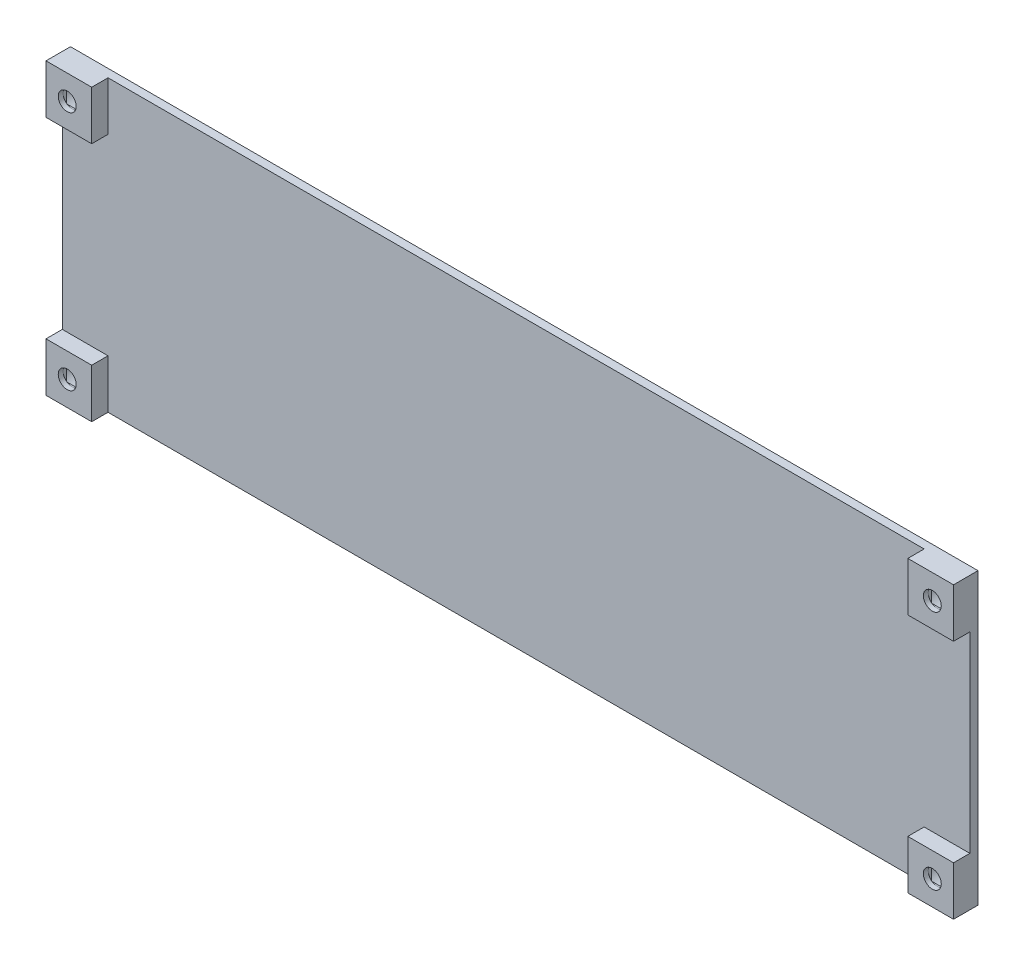
SolidWorks part; units mm, degrees
ref_plane "Front Plane" through (0, 0, 0) normal (0, 0, 1) x (1, 0, 0)
ref_plane "Top Plane" through (0, 0, 0) normal (0, 1, 0) x (1, 0, 0)
ref_plane "Right Plane" through (0, 0, 0) normal (1, 0, 0) x (0, 0, -1)
sketch "Sketch1" plane through (0, 0, 0) normal (0, 0, 1) x (1, 0, 0)
  line L1 (-56, -17.75) -> (56, -17.75)
  line L2 (-56, -17.75) -> (-56, 17.75)
  line L3 (-56, 17.75) -> (56, 17.75)
  line L4 (56, -17.75) -> (56, 17.75)
  line L5 (-56, -17.75) -> (56, 17.75) construction
  line L6 (-56, 17.75) -> (56, -17.75) construction
  point P0 (0, 0)
  dimension "D1" = 112
  dimension "D2" = 35.5
extrude "Boss-Extrude1" add sketch "Sketch1" along normal blind 1
sketch "Sketch2" plane through (0, 0, 1) normal (0, 0, 1) x (1, 0, 0)
  line L0 (0, -17.75) -> (0, 17.75) construction
  line L1 (-56, 17.75) -> (-50, 17.75)
  line L2 (-56, 17.75) -> (-56, 11.75)
  line L3 (-56, 11.75) -> (-50, 11.75)
  line L4 (-50, 17.75) -> (-50, 11.75)
  line L5 (-56, -17.75) -> (56, -17.75) construction
  line L6 (56, 17.75) -> (-56, 17.75) construction
  line L7 (-56, 0) -> (56, 0) construction
  line L8 (-56, 17.75) -> (-56, -17.75) construction
  line L9 (56, -17.75) -> (56, 17.75) construction
  line L10 (-50, -17.75) -> (-50, -11.75)
  line L11 (-56, -11.75) -> (-50, -11.75)
  line L12 (-56, -17.75) -> (-56, -11.75)
  line L13 (-56, -17.75) -> (-50, -17.75)
  line L14 (56, -17.75) -> (50, -17.75)
  line L15 (56, -17.75) -> (56, -11.75)
  line L16 (56, -11.75) -> (50, -11.75)
  line L17 (50, -17.75) -> (50, -11.75)
  line L18 (50, 17.75) -> (50, 11.75)
  line L19 (56, 11.75) -> (50, 11.75)
  line L20 (56, 17.75) -> (56, 11.75)
  line L21 (56, 17.75) -> (50, 17.75)
  dimension "D1" = 6
extrude "Boss-Extrude2" add sketch "Sketch2" along normal blind 2
sketch "Sketch3" plane through (0, 0, 3) normal (0, 0, 1) x (1, 0, 0)
  line L0 (-56, 0) -> (56, 0) construction
  line L1 (-56, 11.75) -> (-56, -11.75) construction
  line L2 (56, -11.75) -> (56, 11.75) construction
  line L3 (0, 17.75) -> (0, -17.75) construction
  line L4 (50, 17.75) -> (-50, 17.75) construction
  line L5 (-50, -17.75) -> (50, -17.75) construction
  line L6 (-56, 11.75) -> (-50, 17.75) construction
  line L7 (-56, -11.75) -> (-50, -17.75) construction
  line L8 (56, -11.75) -> (50, -17.75) construction
  line L9 (56, 11.75) -> (50, 17.75) construction
  circle A0 centre (-53, 14.75) radius 1.1
  circle A1 centre (-53, -14.75) radius 1.1
  circle A2 centre (53, -14.75) radius 1.1
  circle A3 centre (53, 14.75) radius 1.1
  dimension "D1" = 2.2
extrude "Cut-Extrude1" cut sketch "Sketch3" against normal through all
sketch "Sketch4" plane through (0, 0, 0) normal (0, 0, -1) x (-1, 0, 0)
  circle A0 centre (-53, 14.75) radius 2
  circle A1 centre (-53, -14.75) radius 2
  circle A2 centre (53, 14.75) radius 2
  circle A3 centre (53, -14.75) radius 2
  dimension "D1" = 4
extrude "Cut-Extrude2" cut sketch "Sketch4" against normal blind 2
sketch "Sketch5" plane through (0, 0, 2) normal (0, 0, -1) x (-1, 0, 0)
  line L2 (-54.1, 13.0797) -> (-54.1, 16.4203)
  line L4 (-51.9, 13.0797) -> (-51.9, 16.4203)
  line L5 (-54.1, 13.0797) -> (-51.9, 16.4203) construction
  line L6 (-54.1, 16.4203) -> (-51.9, 13.0797) construction
  circle A0 centre (-53, 14.75) radius 2 construction
  circle A1 centre (-53, 14.75) radius 1.1 construction
  circle A2 centre (-53, 14.75) radius 2 construction
  arc A3 (-51.9, 16.4203) -> (-54.1, 16.4203) centre (-53, 14.75) ccw
  arc A4 (-54.1, 13.0797) -> (-51.9, 13.0797) centre (-53, 14.75) ccw
  point P0 (-53, 14.75)
extrude "Cut-Extrude3" cut sketch "Sketch5" against normal blind 0.2
sketch "Sketch6" plane through (0, 0, 2.2) normal (0, 0, -1) x (-1, 0, 0)
  line L0 (-51.9, 13.0797) -> (-51.9, 16.4203) construction
  line L1 (-54.1, 13.65) -> (-51.9, 13.65)
  line L2 (-54.1, 13.65) -> (-54.1, 15.85)
  line L3 (-54.1, 15.85) -> (-51.9, 15.85)
  line L4 (-51.9, 13.65) -> (-51.9, 15.85)
  line L5 (-54.1, 13.65) -> (-51.9, 15.85) construction
  line L6 (-54.1, 15.85) -> (-51.9, 13.65) construction
  arc A0 (-51.9, 14.75) -> (-54.1, 14.75) centre (-53, 14.75) ccw construction
  point P0 (-53, 14.75)
extrude "Cut-Extrude4" cut sketch "Sketch6" against normal blind 0.2
mirror "Mirror1" about plane through (0, 0, 0) normal (1, 0, 0) of "Cut-Extrude4", "Cut-Extrude3"
mirror "Mirror2" about plane through (0, 0, 0) normal (0, 1, 0) of "Mirror1", "Cut-Extrude3", "Cut-Extrude4"
sketch "Sketch7" plane through (0, 0, 0) normal (0, 0, -1) x (-1, 0, 0)
  line L0 (56, -17.75) -> (-56, -17.75) construction
  line L1 (-56, 17.75) -> (-55.6, 17.75)
  line L2 (-56, 17.75) -> (-56, -17.75)
  line L3 (-56, -17.75) -> (-55.6, -17.75)
  line L4 (-55.6, 17.75) -> (-55.6, -17.75)
  line L6 (56, 17.75) -> (55.6, 17.75)
  line L7 (56, 17.75) -> (56, -17.75)
  line L8 (56, -17.75) -> (55.6, -17.75)
  line L9 (55.6, 17.75) -> (55.6, -17.75)
  dimension "D1" = 0.4
extrude "Cut-Extrude5" cut sketch "Sketch7" against normal through all
sketch "Sketch8" plane through (0, 0, 0) normal (0, 0, -1) x (-1, 0, 0)
  line L0 (-55.6, 17.75) -> (55.6, -17.75) construction
  line L1 (-12.5869, -14.75) -> (0, -14.75) construction
  line L2 (55.6, -17.75) -> (-55.6, -17.75) construction
  line L3 (0, 17.75) -> (0, -17.75) construction
  line L4 (-55.6, 17.75) -> (55.6, 17.75) construction
  text T0 "2" font "@HarmonyOS Sans SC" height 28
  point P6 (0, 0)
  point P14 (-11.3282, -14.75)
  point P15 (-16.5919, -14.75)
  point P16 (-12.5869, -14.75)
  dimension "D1" = 3
extrude "Cut-Extrude6" cut sketch "Sketch8" against normal blind 0.2
sketch "Sketch9" plane through (0, 0, 0.2) normal (0, 0, -1) x (-1, 0, 0)
  line L14 (-2.8287, -9.9915) -> (2.102, -4.5072)
  line L15 (-2.8287, -9.9915) -> (2.102, -4.5072)
  line L16 (-2.1866, -1.7351) -> (-10.611, -11.1912)
  line L17 (-10.611, -11.1912) -> (-10.611, -14.65)
  line L18 (-10.611, -14.65) -> (8.5012, -14.65)
  line L19 (8.5012, -14.65) -> (8.5012, -9.9915)
  line L20 (8.5012, -9.9915) -> (-2.8287, -9.9915)
  line L23 (-2.1866, -1.7351) -> (-10.611, -11.1912)
  line L24 (-10.611, -11.1912) -> (-10.611, -14.65)
  line L25 (-10.611, -14.65) -> (8.5012, -14.65)
  line L26 (8.5012, -14.65) -> (8.5012, -9.9915)
  line L27 (8.5012, -9.9915) -> (-2.8287, -9.9915)
  line L28 (-10.7074, 6.7941) -> (-6.5233, 4.3675)
  line L29 (-10.7074, 6.7941) -> (-6.5233, 4.3675)
  spline S6 degree 3 poles (134.6754, 999.4395) (-22.4629, -20.1233) (-9.21, 9.9871) (-0.8114, 8.7043) (-0.5784, 8.6407) (-0.1271, 8.4642) (0.086, 8.3541) (0.4813, 8.0795) (0.663, 7.9142) (0.9853, 7.5568) (1.1295, 7.3602) (1.3683, 6.939) (1.4627, 6.718) (1.6114, 6.2594) (1.6646, 6.0208) (2.787, -3.066) (-25.3418, -15.1284) (998.2361, 88.5106) knots -4.199783 -4.199783 -4.199783 -4.199783 0.125 0.125 0.25 0.25 0.375 0.375 0.5 0.5 0.625 0.625 0.75 0.75 0.875 0.875 5.500499 5.500499 5.500499 5.500499 only from (-1.7636, 8.7959) to (1.74, 5.0597)
  spline S7 degree 3 poles (-1.7636, 8.7959) (-1.5234, 8.7862) (-1.2832, 8.7764) (-0.8114, 8.7043) (-0.5784, 8.6407) (-0.1271, 8.4642) (0.086, 8.3541) (0.4813, 8.0795) (0.663, 7.9142) (0.9853, 7.5568) (1.1295, 7.3602) (1.3683, 6.939) (1.4627, 6.718) (1.6114, 6.2594) (1.6646, 6.0208) (1.7236, 5.5426) (1.7318, 5.3011) (1.74, 5.0597) knots 0 0 0 0 0.125 0.125 0.25 0.25 0.375 0.375 0.5 0.5 0.625 0.625 0.75 0.75 0.875 0.875 1 1 1 1
  spline S8 degree 3 poles (987.5147, -163.0057) (-15.912, 26.4068) (2.4814, 13.5857) (1.6962, 4.3911) (1.6745, 4.226) (1.5805, 3.7367) (1.4834, 3.4173) (1.1061, 2.476) (0.7514, 1.9108) (0.1676, 1.0972) (-0.0368, 0.8319) (-0.4521, 0.3062) (-0.6602, 0.0437) (-17.2797, -20.0408) (-56.7033, -20.5267) (712.8802, -700.7896) knots -3.326313 -3.326313 -3.326313 -3.326313 0.0625 0.0625 0.125 0.125 0.25 0.25 0.5 0.5 0.625 0.625 0.75 0.75 10.356881 10.356881 10.356881 10.356881 only from (1.74, 5.0597) to (-2.1866, -1.7351)
  spline S9 degree 3 poles (1.74, 5.0597) (1.7323, 4.8919) (1.7246, 4.7241) (1.6962, 4.3911) (1.6745, 4.226) (1.5805, 3.7367) (1.4834, 3.4173) (1.1061, 2.476) (0.7514, 1.9108) (0.1676, 1.0972) (-0.0368, 0.8319) (-0.4521, 0.3062) (-0.6602, 0.0437) (-1.3006, -0.7302) (-1.7431, -1.233) (-2.1866, -1.7351) knots 0 0 0 0 0.0625 0.0625 0.125 0.125 0.25 0.25 0.5 0.5 0.625 0.625 0.75 0.75 1 1 1 1
  spline S10 degree 3 poles (711.026, -709.7907) (-45.727, -28.2949) (-13.4715, -22.6013) (3.3616, -3.0687) (3.6685, -2.7022) (4.2695, -1.9583) (4.5642, -1.582) (5.142, -0.8207) (5.4158, -0.429) (5.9442, 0.3687) (6.1932, 0.7759) (6.6239, 1.6215) (6.8069, 2.0598) (7.0282, 2.7427) (7.0935, 2.9743) (7.2061, 3.4383) (7.2532, 3.6715) (9.2852, 16.9529) (-30.4418, 35.965) (1001.9812, -98.3208) knots -6.493203 -6.493203 -6.493203 -6.493203 0.125 0.125 0.25 0.25 0.375 0.375 0.5 0.5 0.625 0.625 0.75 0.75 0.8125 0.8125 0.875 0.875 4.346627 4.346627 4.346627 4.346627 only from (2.102, -4.5072) to (7.3944, 5.3314)
  spline S11 degree 3 poles (2.102, -4.5072) (2.4198, -4.1501) (2.7375, -3.7928) (3.3616, -3.0687) (3.6685, -2.7022) (4.2695, -1.9583) (4.5642, -1.582) (5.142, -0.8207) (5.4158, -0.429) (5.9442, 0.3687) (6.1932, 0.7759) (6.6239, 1.6215) (6.8069, 2.0598) (7.0282, 2.7427) (7.0935, 2.9743) (7.2061, 3.4383) (7.2532, 3.6715) (7.361, 4.3762) (7.3788, 4.8537) (7.3944, 5.3314) knots 0 0 0 0 0.125 0.125 0.25 0.25 0.375 0.375 0.5 0.5 0.625 0.625 0.75 0.75 0.8125 0.8125 0.875 0.875 1 1 1 1
  spline S12 degree 3 poles (998.9416, 135.0241) (-13.1864, -24.171) (8.262, -7.0923) (7.338, 6.4538) (7.3076, 6.7317) (7.172, 7.5575) (7.0242, 8.0996) (6.6173, 9.1596) (6.3658, 9.6622) (5.7547, 10.6058) (5.3883, 11.0491) (4.5734, 11.8215) (4.1245, 12.159) (3.1504, 12.7444) (2.6394, 12.9802) (1.8421, 13.2558) (1.5718, 13.3366) (1.0193, 13.4683) (0.741, 13.5177) (0.1833, 13.6038) (-0.0968, 13.6357) (-12.5963, 14.4477) (-27.6337, -10.3518) (72.5754, 1010.9536) knots -2.90139 -2.90139 -2.90139 -2.90139 0.0625 0.0625 0.125 0.125 0.25 0.25 0.375 0.375 0.5 0.5 0.625 0.625 0.75 0.75 0.8125 0.8125 0.875 0.875 0.9375 0.9375 3.649243 3.649243 3.649243 3.649243 only from (7.3944, 5.3314) to (-1.2263, 13.6812)
  spline S13 degree 3 poles (7.3944, 5.3314) (7.3853, 5.6129) (7.3762, 5.8943) (7.338, 6.4538) (7.3076, 6.7317) (7.172, 7.5575) (7.0242, 8.0996) (6.6173, 9.1596) (6.3658, 9.6622) (5.7547, 10.6058) (5.3883, 11.0491) (4.5734, 11.8215) (4.1245, 12.159) (3.1504, 12.7444) (2.6394, 12.9802) (1.8421, 13.2558) (1.5718, 13.3366) (1.0193, 13.4683) (0.741, 13.5177) (0.1833, 13.6038) (-0.0968, 13.6357) (-0.66, 13.6723) (-0.9431, 13.677) (-1.2263, 13.6812) knots 0 0 0 0 0.0625 0.0625 0.125 0.125 0.25 0.25 0.375 0.375 0.5 0.5 0.625 0.625 0.75 0.75 0.8125 0.8125 0.875 0.875 0.9375 0.9375 1 1 1 1
  spline S14 degree 3 poles (-128.4205, 1005.5575) (26.5417, -7.3008) (10.4115, 14.3687) (-2.2795, 13.641) (-2.5403, 13.6155) (-3.3177, 13.5095) (-3.8297, 13.4009) (-4.5876, 13.177) (-4.8396, 13.0911) (-5.3337, 12.9018) (-5.5758, 12.7988) (-6.0473, 12.5715) (-6.2766, 12.447) (-6.7259, 12.1822) (-6.9458, 12.0419) (-7.3754, 11.744) (-7.5851, 11.5866) (-7.9901, 11.2472) (-8.1856, 11.0645) (-8.5583, 10.6893) (-8.7365, 10.4955) (-9.0684, 10.0891) (-9.2224, 9.8769) (-9.517, 9.4423) (-9.6573, 9.2197) (-9.9194, 8.7604) (-10.0414, 8.5231) (-10.2626, 8.0414) (-10.3623, 7.7962) (-14.9767, -4.8254) (2.506, -25.9407) (-953.6389, 339.7362) knots -2.89677 -2.89677 -2.89677 -2.89677 0.0625 0.0625 0.125 0.125 0.25 0.25 0.3125 0.3125 0.375 0.375 0.4375 0.4375 0.5 0.5 0.5625 0.5625 0.625 0.625 0.6875 0.6875 0.75 0.75 0.8125 0.8125 0.875 0.875 0.9375 0.9375 4.047221 4.047221 4.047221 4.047221 only from (-1.2263, 13.6812) to (-10.7074, 6.7941)
  spline S15 degree 3 poles (-1.2263, 13.6812) (-1.4904, 13.6762) (-1.7545, 13.6711) (-2.2795, 13.641) (-2.5403, 13.6155) (-3.3177, 13.5095) (-3.8297, 13.4009) (-4.5876, 13.177) (-4.8396, 13.0911) (-5.3337, 12.9018) (-5.5758, 12.7988) (-6.0473, 12.5715) (-6.2766, 12.447) (-6.7259, 12.1822) (-6.9458, 12.0419) (-7.3754, 11.744) (-7.5851, 11.5866) (-7.9901, 11.2472) (-8.1856, 11.0645) (-8.5583, 10.6893) (-8.7365, 10.4955) (-9.0684, 10.0891) (-9.2224, 9.8769) (-9.517, 9.4423) (-9.6573, 9.2197) (-9.9194, 8.7604) (-10.0414, 8.5231) (-10.2626, 8.0414) (-10.3623, 7.7962) (-10.5442, 7.2988) (-10.6262, 7.0466) (-10.7074, 6.7941) knots 0 0 0 0 0.0625 0.0625 0.125 0.125 0.25 0.25 0.3125 0.3125 0.375 0.375 0.4375 0.4375 0.5 0.5 0.5625 0.5625 0.625 0.625 0.6875 0.6875 0.75 0.75 0.8125 0.8125 0.875 0.875 0.9375 0.9375 1 1 1 1
  spline S16 degree 3 poles (-923.4536, 403.4073) (10.7122, -30.6272) (-10.8569, -6.4394) (-6.1248, 5.4591) (-6.0028, 5.7212) (-5.7308, 6.2321) (-5.582, 6.4814) (-5.2482, 6.9627) (-5.0642, 7.191) (-4.6641, 7.6126) (-4.448, 7.808) (-3.9753, 8.1585) (-3.7251, 8.307) (-3.1974, 8.5515) (-2.9169, 8.6501) (5.7449, 10.4283) (19.7944, -25.7452) (-125.2937, 1001.1101) knots -5.272899 -5.272899 -5.272899 -5.272899 0.125 0.125 0.25 0.25 0.375 0.375 0.5 0.5 0.625 0.625 0.75 0.75 0.875 0.875 4.548664 4.548664 4.548664 4.548664 only from (-6.5233, 4.3675) to (-1.7636, 8.7959)
  spline S17 degree 3 poles (-6.5233, 4.3675) (-6.4321, 4.6445) (-6.339, 4.9205) (-6.1248, 5.4591) (-6.0028, 5.7212) (-5.7308, 6.2321) (-5.582, 6.4814) (-5.2482, 6.9627) (-5.0642, 7.191) (-4.6641, 7.6126) (-4.448, 7.808) (-3.9753, 8.1585) (-3.7251, 8.307) (-3.1974, 8.5515) (-2.9169, 8.6501) (-2.3469, 8.7672) (-2.0553, 8.7818) (-1.7636, 8.7959) knots 0 0 0 0 0.125 0.125 0.25 0.25 0.375 0.375 0.5 0.5 0.625 0.625 0.75 0.75 0.875 0.875 1 1 1 1
  dimension "D1" = 0.1
extrude "Boss-Extrude3" add sketch "Sketch9" along normal up to surface (0.2 mm away) up to face at (0, 0, 0)
